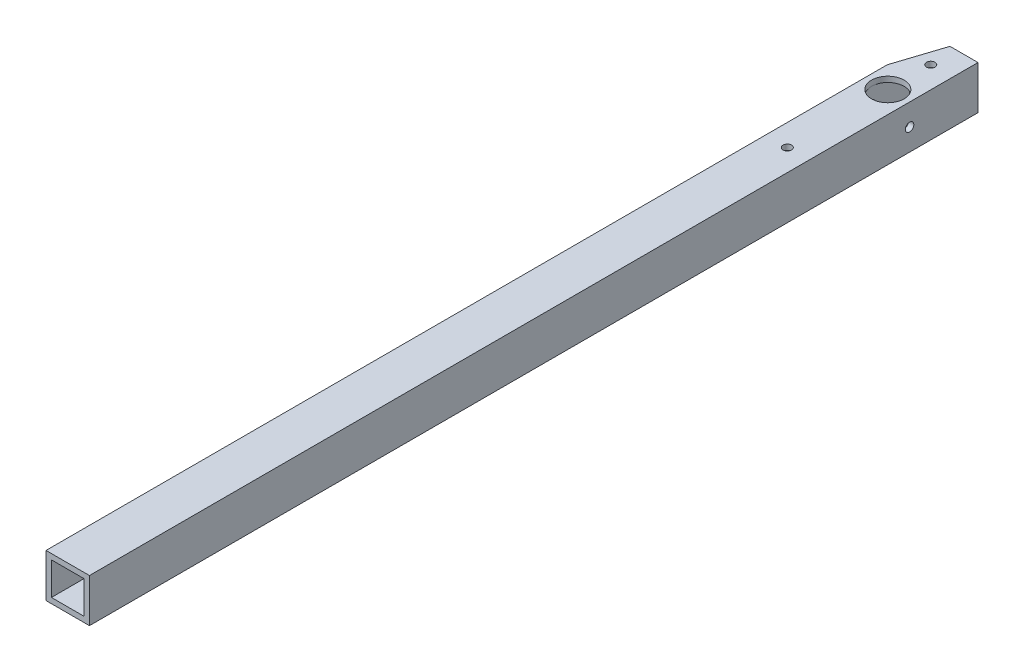
SolidWorks part; units mm, degrees
ref_plane "Front Plane" through (0, 0, 0) normal (0, 0, 1) x (1, 0, 0)
ref_plane "Top Plane" through (0, 0, 0) normal (0, 1, 0) x (1, 0, 0)
ref_plane "Right Plane" through (0, 0, 0) normal (1, 0, 0) x (0, 0, -1)
sketch "Sketch1" plane through (0, 0, 0) normal (0, 0, 1) x (1, 0, 0)
  line L0 (-9.525, 9.525) -> (9.525, 9.525)
  line L2 (-12.7, 12.7) -> (12.7, 12.7)
  line L3 (-12.7, 12.7) -> (-12.7, -12.7)
  line L4 (-12.7, -12.7) -> (12.7, -12.7)
  line L5 (12.7, 12.7) -> (12.7, -12.7)
  line L10 (9.525, 9.525) -> (9.525, -9.525)
  line L11 (-9.525, -9.525) -> (9.525, -9.525)
  line L12 (-9.525, 9.525) -> (-9.525, -9.525)
  point P12 (0, 12.7)
  point P14 (12.7, 0)
  dimension "Wall Thickness" = 3.175
  dimension "Outside Width" = 25.4
  dimension "Outside Height" = 25.4
  dimension "Inside Height" = 19.05
  dimension "Inside Width" = 19.05
sketch "Sketch2" plane through (0, 0, 0) normal (1, 0, 0) x (0, 0, -1)
  line L0 (266.7, 0) -> (-266.7, 0)
  point P4 (0, 0)
  point P7 (-266.7, 0)
  point P10 (266.7, 0)
  dimension "Length" = 533.4
sketch "Sketch3" plane through (0, 0, 0) normal (0, 0, 1) x (1, 0, 0)
  line L21 (12.7, 12.7) -> (-12.7, 12.7)
  line L22 (12.7, -12.7) -> (12.7, 12.7)
  line L23 (-12.7, -12.7) -> (12.7, -12.7)
  line L24 (-12.7, 12.7) -> (-12.7, -12.7)
  line L25 (12.7, 12.7) -> (-12.7, 12.7)
  line L26 (12.7, -12.7) -> (12.7, 12.7)
  line L27 (-12.7, -12.7) -> (12.7, -12.7)
  line L28 (-12.7, 12.7) -> (-12.7, -12.7)
  line L29 (9.525, 9.525) -> (-9.525, 9.525)
  line L30 (9.525, -9.525) -> (9.525, 9.525)
  line L31 (-9.525, -9.525) -> (9.525, -9.525)
  line L32 (-9.525, 9.525) -> (-9.525, -9.525)
  line L33 (9.525, 9.525) -> (-9.525, 9.525)
  line L34 (9.525, -9.525) -> (9.525, 9.525)
  line L35 (-9.525, -9.525) -> (9.525, -9.525)
  line L36 (-9.525, 9.525) -> (-9.525, -9.525)
  dimension "D1" = 0
  dimension "D2" = 0
extrude "Boss-Extrude1" add sketch "Sketch3" along normal up to vertex (266.7 mm away) and the other way up to vertex (266.7 mm away) up to point (0, 0, 266.7) other way up to point (0, 0, -266.7)
sketch "Drawing Reference" plane through (0, 0, 0) normal (1, 0, 0) x (0, 0, -1)
  line L0 (-266.7, 0) -> (266.7, 0) construction
  line L1 (0, -12.7) -> (0, 12.7) construction
  line L2 (-266.7, -12.7) -> (266.7, -12.7) construction
  line L5 (-266.7, 12.7) -> (266.7, 12.7) construction
  point P7 (-248.412, 0)
  point P8 (248.412, 0)
  dimension "D1" = 18.288
sketch "Sketch4" plane through (0, 12.7, 0) normal (0, 1, 0) x (1, 0, 0)
  line L1 (0, 266.7) -> (0, 212.725) construction
  line L7 (-12.7, 225.0135) -> (-12.7, 266.7)
  line L8 (-188.9197, -317.3351) -> (4.6184, 278.3139) construction
  line L10 (-12.7, -266.7) -> (-12.7, 266.7) construction
  line L11 (-12.7, 266.7) -> (12.7, 266.7)
  line L12 (12.7, 266.7) -> (12.7, 252.73)
  line L13 (12.7, -266.7) -> (12.7, 266.7) construction
  line L14 (12.7, 252.73) -> (-3.6943, 252.73)
  line L15 (-3.6943, 252.73) -> (-12.7, 225.0135)
  circle A0 centre (0, 212.725) radius 9.525
  dimension "D1" = 13.97
extrude "Cut-Extrude1" cut sketch "Sketch4" against normal blind 25.4
sketch "Sketch5" plane through (0, -12.7, 0) normal (0, -1, 0) x (1, 0, 0)
  circle A0 centre (-0.6605, -179.8709) radius 9.525
extrude "Cut-Extrude2" cut sketch "Sketch5" against normal blind 3.175
sketch "Sketch6" plane through (12.7, 0, 0) normal (1, 0, 0) x (0, 0, -1)
  line L0 (252.73, 0) -> (212.725, 0) construction
  line L1 (252.73, -12.7) -> (252.73, 12.7) construction
hole_wizard "#10 Clearance Hole1" positions "Sketch7" profile "Sketch8" hole size "#10" standard "ANSI Inch" end condition through all
sketch "Sketch7" plane through (12.7, 0, 0) normal (1, 0, 0) x (0, 0, -1)
  point P0 (212.725, 0)
sketch "Sketch8" plane through (12.7, 0, -212.725) normal (0, 1, 0) x (0, 0, -1)
  line L0 (0, 0) -> (0, 25.4)
  line L1 (0, 25.4) -> (2.4892, 25.4)
  line L2 (2.4892, 25.4) -> (2.4892, 0)
  line L5 (2.4892, 0) -> (0, 0)
  line L11 (0, -6.35) -> (0, 107.95) construction
  dimension "Thru Hole Dia." = 4.9784
  dimension "Thru Hole Depth" = 25.4
hole_wizard "#10 Clearance Hole2" positions "Sketch9" profile "Sketch10" hole size "#10" standard "ANSI Inch" end condition through all
sketch "Sketch9" plane through (0, 12.7, 0) normal (0, 1, 0) x (1, 0, 0)
  point P0 (0, 153.96)
  point P3 (0, 237.8065)
sketch "Sketch10" plane through (0, 12.7, -153.96) normal (1, 0, 0) x (0, 0, 1)
  line L0 (0, 0) -> (0, 25.4)
  line L1 (0, 25.4) -> (2.4892, 25.4)
  line L2 (2.4892, 25.4) -> (2.4892, 0)
  line L5 (2.4892, 0) -> (0, 0)
  line L11 (0, -6.35) -> (0, 107.95) construction
  dimension "Thru Hole Dia." = 4.9784
  dimension "Thru Hole Depth" = 25.4
equation "\"D1@Drawing Reference\"=\"Outside Width@Sketch1\" * 0.72"
